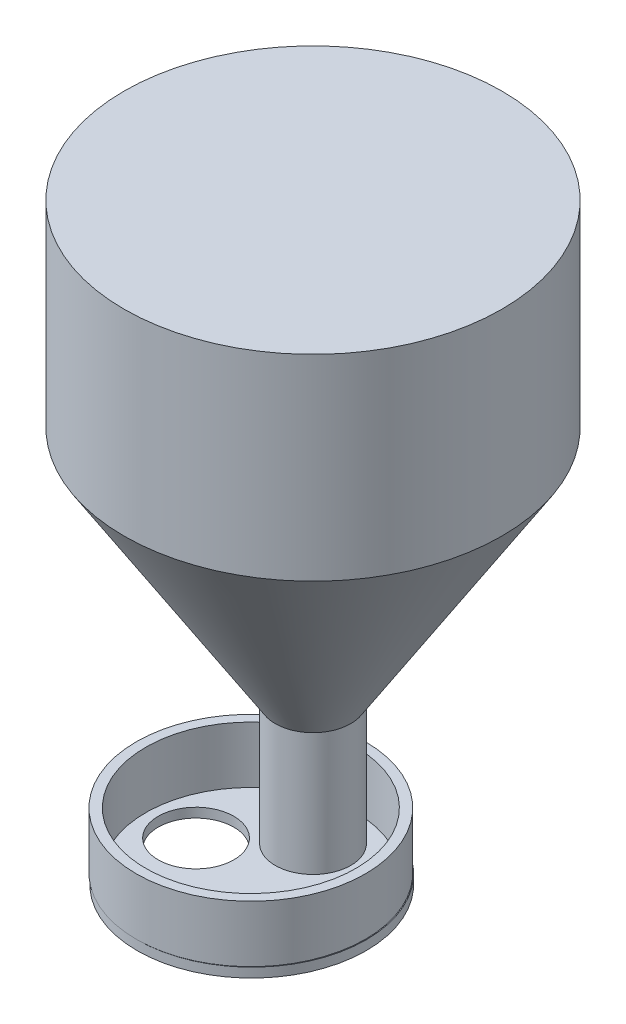
SolidWorks part; units mm, degrees
ref_plane "Alzado" through (0, 0, 0) normal (0, 0, 1) x (1, 0, 0)
ref_plane "Planta" through (0, 0, 0) normal (0, 1, 0) x (1, 0, 0)
ref_plane "Vista lateral" through (0, 0, 0) normal (1, 0, 0) x (0, 0, -1)
sketch "Croquis1" plane through (0, 0, 0) normal (0, 1, 0) x (1, 0, 0)
  circle A0 centre (0, 0) radius 100
  dimension "D1" = 200
ref_plane "Plano1" through (0, -230, 0) normal (0, 1, 0) x (1, 0, 0)
extrude "Saliente-Extruir1" add sketch "Croquis1" against normal blind 104 contours A0
sketch "Croquis2" plane through (0, -104, 0) normal (0, -1, 0) x (1, 0, 0)
  circle A2 centre (0, 0) radius 100
sketch "Croquis3" plane through (0, -230, 0) normal (0, 1, 0) x (1, 0, 0)
  circle A0 centre (0, 0) radius 20
  dimension "D1" = 40
loft "Recubrir1" add profiles "Croquis3", "Croquis2"
sketch "Croquis4" plane through (0, -230, 0) normal (0, -1, 0) x (1, 0, 0)
  circle A0 centre (0, 0) radius 20
  dimension "D1" = 40
extrude "Saliente-Extruir2" add sketch "Croquis4" along normal blind 65
ref_plane "Plano2" through (0, 0, -20) normal (0, 0, -1) x (-1, 0, 0)
sketch "Croquis7" plane through (0, -295, 0) normal (0, -1, 0) x (1, 0, 0)
  circle A0 centre (0, 0) radius 17.5
  dimension "D1" = 35
extrude "Cortar-Extruir2" cut sketch "Croquis7" against normal blind 24
sketch "Croquis8" plane through (0, -295, 0) normal (0, -1, 0) x (1, 0, 0)
  circle A0 centre (-32.8935, 0) radius 60.6028
  circle A1 centre (-32.8935, 0) radius 55.6028
  point P5 (-32.8935, 0)
  dimension "D1" = 5
extrude "Saliente-Extruir3" add sketch "Croquis8" along normal blind 30 separate body
sketch "Croquis9" plane through (0, -295, 0) normal (0, 1, 0) x (1, 0, 0)
  circle A0 centre (-32.4436, 0) radius 60.6028
  point P3 (-32.4436, 0)
sketch "Croquis10" plane through (0, -325, 0) normal (0, -1, 0) x (1, 0, 0)
  circle A0 centre (-32.4436, 0) radius 60.6028
  circle A1 centre (-63.5378, -1.6179) radius 20
  dimension "D1" = 40
extrude "Saliente-Extruir5" add sketch "Croquis10" along normal blind 5
